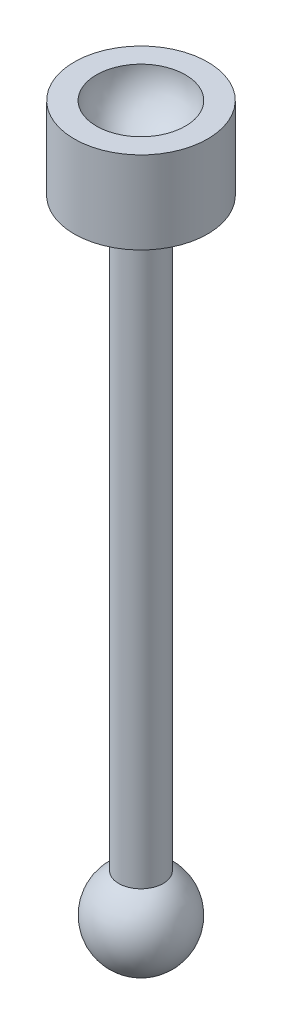
SolidWorks part; units mm, degrees
ref_plane "Front Plane" through (0, 0, 0) normal (0, 0, 1) x (1, 0, 0)
ref_plane "Top Plane" through (0, 0, 0) normal (0, 1, 0) x (1, 0, 0)
ref_plane "Right Plane" through (0, 0, 0) normal (1, 0, 0) x (0, 0, -1)
sketch "Sketch1" plane through (0, 0, 0) normal (0, 0, 1) x (1, 0, 0)
  line L0 (0, 41.7343) -> (0, -126.926) construction
  line L1 (0, 41.7343) -> (5, 41.7343)
  line L2 (5, 41.7343) -> (5, -108.2657)
  line L3 (0, 41.7343) -> (0, -126.926)
  arc A0 (5, -108.2657) -> (0, -126.926) centre (0, -116.926) cw
  point P1 (4.2979, -108.2657)
  point P7 (0, -44.7926)
  point P8 (0, 0)
  point P9 (0, 0)
  point P10 (0, 0)
  dimension "D1" = 10
  dimension "D2" = 5
  dimension "D3" = 150
revolve "Revolve1" add sketch "Sketch1" angle 360 about L0
sketch "Sketch3" plane through (0, 0, 0) normal (0, 0, 1) x (1, 0, 0)
  line L0 (0, 41.7343) -> (0, 23.214) construction
  line L1 (5, 41.7343) -> (-5, 41.7343) construction
  line L2 (0, 23.214) -> (15, 23.214)
  line L3 (0, 41.7343) -> (0, 23.214)
  line L4 (15, 23.214) -> (15, 41.7343)
  line L5 (15, 41.7343) -> (0, 41.7343)
  line L6 (0, 41.7343) -> (0, 23.214) construction
  point P5 (0.1756, 41.7343)
  point P11 (5, 41.7343)
  dimension "D1" = 15
revolve "Revolve3" add sketch "Sketch3" angle 360 about L0
sketch "Sketch5" plane through (0, 0, 0) normal (0, 0, 1) x (1, 0, 0)
  line L0 (0, 41.7343) -> (0, 31.7343) construction
  line L1 (15, 41.7343) -> (-15, 41.7343) construction
  line L2 (0, 41.7343) -> (0, 31.7343)
  line L3 (0, 41.7343) -> (10, 41.7343)
  arc A0 (0, 31.7343) -> (10, 41.7343) centre (0, 41.7343) ccw
  dimension "D1" = 10
revolve "Cut-Revolve2" cut sketch "Sketch5" angle 360 about L0
